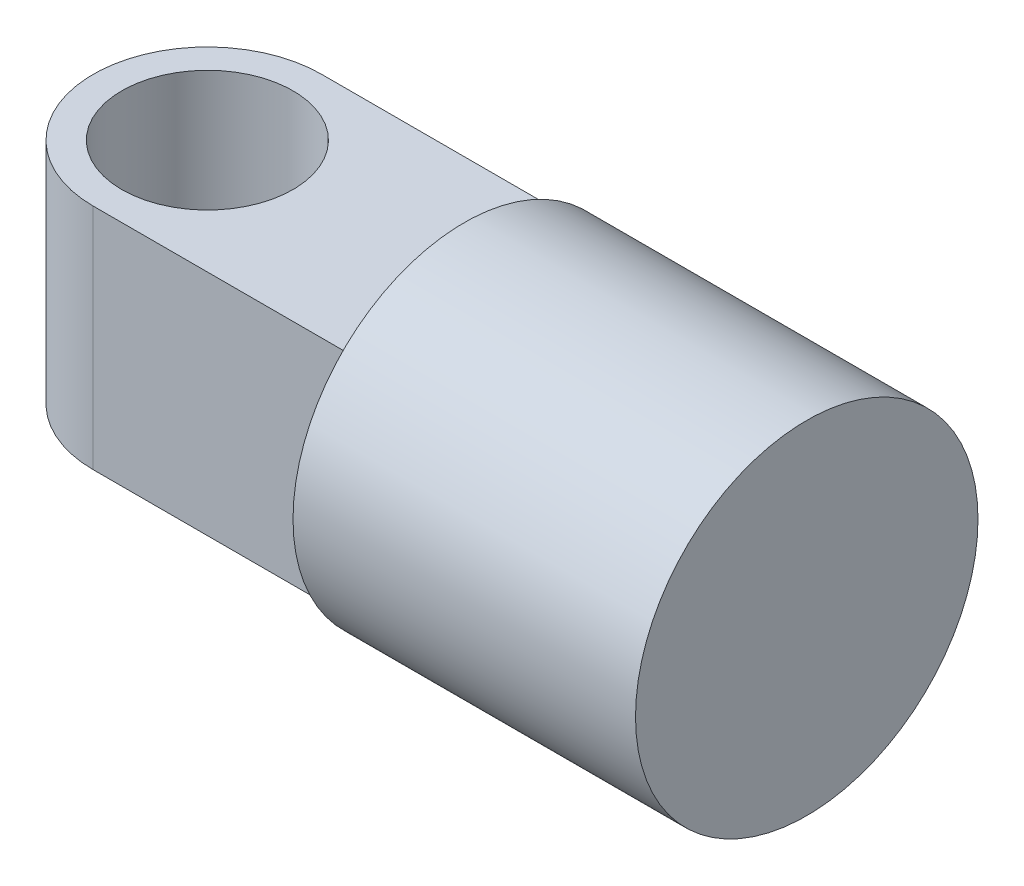
SolidWorks part; units mm, degrees
ref_plane "Front Plane" through (0, 0, 0) normal (0, 0, 1) x (1, 0, 0)
ref_plane "Top Plane" through (0, 0, 0) normal (0, 1, 0) x (1, 0, 0)
ref_plane "Right Plane" through (0, 0, 0) normal (1, 0, 0) x (0, 0, -1)
sketch "Sketch1" plane through (0, 0, 0) normal (0, 1, 0) x (1, 0, 0)
  line L0 (0, 0) -> (-25.4, 0) construction
  line L1 (0, 0) -> (25.4, 0) construction
  line L2 (0, 0) -> (0, -25.4) construction
  line L3 (0, 0) -> (0, 25.4) construction
  line L4 (0, -25.4) -> (57.15, -25.4)
  line L5 (0, 25.4) -> (57.15, 25.4)
  line L6 (57.15, 25.4) -> (57.15, -25.4)
  circle A0 centre (0, 0) radius 19.05
  circle A1 centre (0, 0) radius 25.4
  dimension "D1" = 38.1
  dimension "D2" = 50.8
  dimension "D3" = 57.15
  dimension "D4" = 57.15
extrude "Boss-Extrude1" add sketch "Sketch1" along normal blind 50.8 contours A1 L4 L6 L5 | A1 A0
sketch "Sketch2" plane through (57.15, 0, 0) normal (1, 0, 0) x (0, 0, -1)
  line L0 (-25.4, 50.8) -> (25.4, 0) construction
  line L1 (-25.4, 0) -> (25.4, 50.8) construction
  line L2 (25.4, 50.8) -> (-25.4, 50.8) construction
  circle A0 centre (0, 25.4) radius 38.1
  dimension "D1" = 76.2
extrude "Boss-Extrude2" add sketch "Sketch2" along normal blind 76.2
